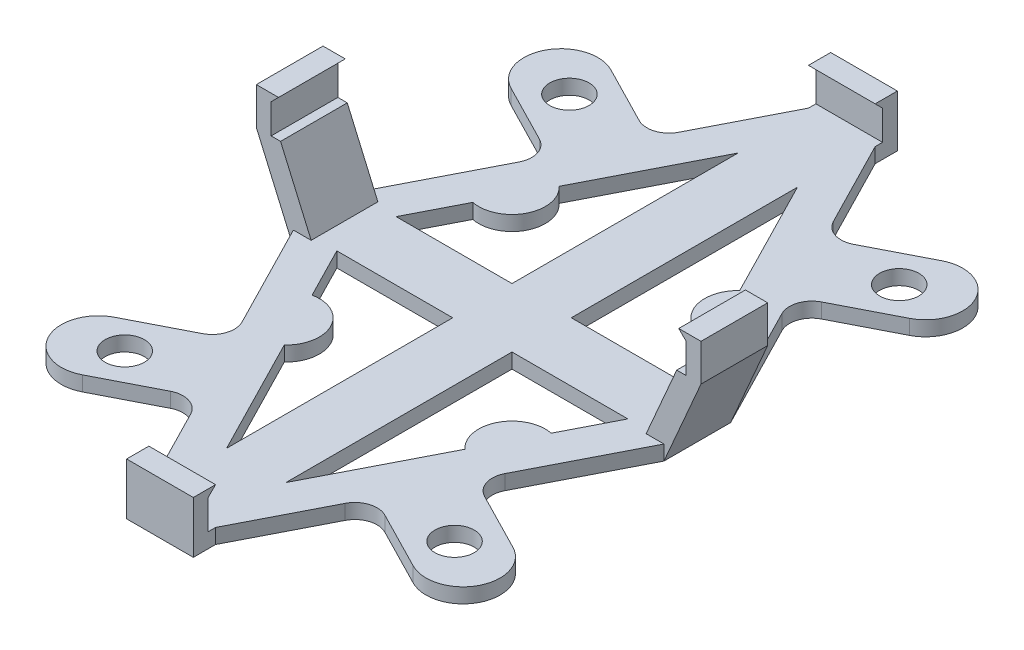
SolidWorks part; units mm, degrees
material "PLA"
ref_plane "Front Plane" through (0, 0, 0) normal (0, 0, 1) x (1, 0, 0)
ref_plane "Top Plane" through (0, 0, 0) normal (0, 1, 0) x (1, 0, 0)
ref_plane "Right Plane" through (0, 0, 0) normal (1, 0, 0) x (0, 0, -1)
sketch "Sketch1" plane through (0, 0, 0) normal (0, 1, 0) x (1, 0, 0)
  line L0 (-762.7074, 0) -> (37372.6612, 0) construction
  line L1 (0, -762.7074) -> (0, 37372.6612) construction
  line L2 (4.5, 47.5) -> (-4.5, 47.5)
  line L3 (-4.5, 47.5) -> (-4.5, 44.5)
  line L4 (-4.5, 44.5) -> (-10.429, 32.9312)
  line L6 (-25, 4.5) -> (-25, -4.5)
  line L7 (-4, 34.5129) -> (-12.1841, 18.544)
  line L8 (-19.6379, 4) -> (-4, 4)
  line L9 (-4, 4) -> (-4, 34.5129)
  line L10 (4, 4) -> (4, 34.5129)
  line L11 (19.6379, 4) -> (4, 4)
  line L12 (4, 34.5129) -> (12.1841, 18.544)
  line L13 (25, 4.5) -> (25, -4.5)
  line L15 (4.5, 44.5) -> (10.429, 32.9312)
  line L16 (4.5, 47.5) -> (4.5, 44.5)
  line L17 (4.5, -47.5) -> (4.5, -44.5)
  line L18 (4.5, -44.5) -> (10.429, -32.9312)
  line L20 (4, -34.5129) -> (12.1841, -18.544)
  line L21 (19.6379, -4) -> (4, -4)
  line L22 (4, -4) -> (4, -34.5129)
  line L23 (-4, -4) -> (-4, -34.5129)
  line L24 (-19.6379, -4) -> (-4, -4)
  line L25 (-4, -34.5129) -> (-12.1841, -18.544)
  line L27 (-4.5, -44.5) -> (-10.429, -32.9312)
  line L28 (-4.5, -47.5) -> (-4.5, -44.5)
  line L29 (4.5, -47.5) -> (-4.5, -47.5)
  line L30 (-14.4671, 31.6297) -> (-22.3279, 35.6583)
  line L31 (22.25, -30) -> (-22.25, -30) construction
  line L32 (22.25, -30) -> (22.25, 30) construction
  line L33 (22.25, 30) -> (-22.25, 30) construction
  line L34 (-22.25, -30) -> (-22.25, 30) construction
  line L35 (22.25, -30) -> (-22.25, 30) construction
  line L36 (22.25, 30) -> (-22.25, -30) construction
  line L37 (-22.3279, 35.6583) -> (-26.8888, 26.759) construction
  line L38 (-26.8888, 26.759) -> (-19.028, 22.7303)
  line L39 (-24.6083, 31.2086) -> (-22.25, 30) construction
  line L40 (-26.8888, -26.759) -> (-19.028, -22.7303)
  line L41 (-14.4671, -31.6297) -> (-22.3279, -35.6583)
  line L42 (14.4671, 31.6297) -> (22.3279, 35.6583)
  line L43 (26.8888, 26.759) -> (19.028, 22.7303)
  line L44 (14.4671, -31.6297) -> (22.3279, -35.6583)
  line L45 (26.8888, -26.759) -> (19.028, -22.7303)
  line L46 (11.9312, 30) -> (16.1479, 21.7724) construction
  line L47 (17.7265, 18.6923) -> (17.4906, 19.1525) construction
  line L48 (-11.9312, 30) -> (-16.1479, 21.7724) construction
  line L49 (-17.7265, 18.6923) -> (-17.4906, 19.1525) construction
  line L50 (-11.7973, 30.2614) -> (-11.9312, 30) construction
  line L51 (-16.1479, 21.7724) -> (-16.3582, 21.3621) construction
  line L52 (-11.9312, -30) -> (-16.1479, -21.7724) construction
  line L53 (-17.7265, -18.6923) -> (-17.4906, -19.1525) construction
  line L54 (-16.1479, -21.7724) -> (-16.3582, -21.3621) construction
  line L55 (-11.7973, -30.2614) -> (-11.9312, -30) construction
  line L56 (16.1479, 21.7724) -> (16.3582, 21.3621) construction
  line L57 (11.7973, 30.2614) -> (11.9312, 30) construction
  line L58 (11.9312, -30) -> (16.1479, -21.7724) construction
  line L59 (17.7265, -18.6923) -> (17.4906, -19.1525) construction
  line L60 (16.1479, -21.7724) -> (16.3582, -21.3621) construction
  line L61 (11.7973, -30.2614) -> (11.9312, -30) construction
  line L62 (16.1336, -10.8376) -> (19.6379, -4)
  line L63 (-15.25, 15.25) -> (15.25, 15.25) construction
  line L64 (-15.25, 15.25) -> (-15.25, -15.25) construction
  line L65 (-15.25, -15.25) -> (15.25, -15.25) construction
  line L66 (15.25, 15.25) -> (15.25, -10.75) construction
  line L67 (-15.25, 15.25) -> (14.3391, -14.3391) construction
  line L68 (-15.25, -15.25) -> (15.25, 15.25) construction
  line L69 (-13.8722, -15.25) -> (-14.3391, -14.3391) construction
  line L70 (-16.1336, -10.8376) -> (-19.6379, -4)
  line L71 (-16.1336, 10.8376) -> (-19.6379, 4)
  line L72 (16.1336, 10.8376) -> (19.6379, 4)
  line L73 (19.7264, -14.7899) -> (25, -4.5)
  line L74 (22.25, -9.8659) -> (19.7264, -14.7899) construction
  line L75 (17.4906, -19.1525) -> (22.25, -9.8659) construction
  line L76 (19.7264, 14.7899) -> (25, 4.5)
  line L77 (22.25, 9.8659) -> (19.7264, 14.7899) construction
  line L78 (17.4906, 19.1525) -> (22.25, 9.8659) construction
  line L79 (-19.7264, -14.7899) -> (-25, -4.5)
  line L80 (-22.25, -9.8659) -> (-19.7264, -14.7899) construction
  line L81 (-17.4906, -19.1525) -> (-17.7265, -18.6923) construction
  line L82 (-19.7264, 14.7899) -> (-25, 4.5)
  line L83 (-22.25, 9.8659) -> (-19.7264, 14.7899) construction
  line L84 (-17.4906, 19.1525) -> (-22.25, 9.8659) construction
  line L85 (-19.7264, -14.7899) -> (-22.25, -9.8659) construction
  line L86 (-17.7265, -18.6923) -> (-19.7264, -14.7899) construction
  line L87 (-17.7265, -18.6923) -> (-19.7264, -14.7899)
  line L88 (17.7265, -18.6923) -> (19.7264, -14.7899)
  line L89 (19.7264, 14.7899) -> (17.7265, 18.6923)
  line L90 (-19.7264, 14.7899) -> (-17.7265, 18.6923)
  circle A0 centre (-22.25, 30) radius 2.65
  arc A1 (-22.3279, 35.6583) -> (-26.8888, 26.759) centre (-24.6083, 31.2086) ccw
  circle A2 centre (-22.25, -30) radius 2.65
  arc A3 (-22.3279, -35.6583) -> (-26.8888, -26.759) centre (-24.6083, -31.2086) cw
  arc A4 (22.3279, 35.6583) -> (26.8888, 26.759) centre (24.6083, 31.2086) cw
  circle A5 centre (22.25, 30) radius 2.65
  circle A6 centre (22.25, -30) radius 2.65
  arc A7 (22.3279, -35.6583) -> (26.8888, -26.759) centre (24.6083, -31.2086) ccw
  arc A8 (14.4671, -31.6297) -> (10.429, -32.9312) centre (13.0988, -34.2995) ccw
  arc A9 (19.028, -22.7303) -> (17.7265, -18.6923) centre (20.3963, -20.0605) cw
  arc A10 (-10.429, -32.9312) -> (-14.4671, -31.6297) centre (-13.0988, -34.2995) ccw
  arc A11 (-17.7265, -18.6923) -> (-19.028, -22.7303) centre (-20.3963, -20.0605) cw
  arc A12 (-17.7265, 18.6923) -> (-19.028, 22.7303) centre (-20.3963, 20.0605) ccw
  arc A13 (-14.4671, 31.6297) -> (-10.429, 32.9312) centre (-13.0988, 34.2995) ccw
  arc A14 (14.4671, 31.6297) -> (10.429, 32.9312) centre (13.0988, 34.2995) cw
  arc A15 (19.028, 22.7303) -> (17.7265, 18.6923) centre (20.3963, 20.0605) ccw
  arc A16 (13.4822, -13.4822) -> (12.75, -15.25) centre (15.25, -15.25) ccw construction
  arc A17 (-12.75, -15.25) -> (-15.25, -12.75) centre (-15.25, -15.25) cw construction
  arc A18 (13.4822, 13.4822) -> (12.75, 15.25) centre (15.25, 15.25) cw construction
  arc A19 (-12.75, 15.25) -> (-15.25, 12.75) centre (-15.25, 15.25) ccw construction
  arc A20 (16.1336, -10.8376) -> (12.1841, -18.544) centre (15.25, -15.25) ccw
  circle A21 centre (15.25, -15.25) radius 4.5 construction
  arc A22 (-16.1336, -10.8376) -> (-12.1841, -18.544) centre (-15.25, -15.25) cw
  arc A23 (16.1336, 10.8376) -> (12.1841, 18.544) centre (15.25, 15.25) cw
  arc A24 (-16.1336, 10.8376) -> (-12.1841, 18.544) centre (-15.25, 15.25) ccw
  arc A25 (17.5478, -19.1191) -> (19.7264, -14.7899) centre (15.25, -15.25) ccw construction
  arc A26 (17.4906, 19.1525) -> (17.5478, 19.1191) centre (15.25, 15.25) cw construction
  arc A27 (-17.5478, 19.1191) -> (-19.7264, 14.7899) centre (-15.25, 15.25) ccw construction
  arc A28 (-17.4906, -19.1525) -> (-17.5478, -19.1191) centre (-15.25, -15.25) cw construction
  arc A29 (-17.5478, -19.1191) -> (-19.7264, -14.7899) centre (-15.25, -15.25) cw construction
  arc A30 (17.4906, -19.1525) -> (17.5478, -19.1191) centre (15.25, -15.25) ccw construction
  arc A31 (-13.4822, -13.4822) -> (-12.75, -15.25) centre (-15.25, -15.25) cw construction
  arc A32 (12.75, -15.25) -> (13.4822, -13.4822) centre (15.25, -15.25) ccw construction
  circle A33 centre (15.25, -15.25) radius 2.5 construction
  arc A34 (-15.25, -12.75) -> (-13.4822, -13.4822) centre (-15.25, -15.25) cw construction
  arc A35 (12.75, 15.25) -> (15.25, 12.75) centre (15.25, 15.25) cw construction
  arc A36 (17.5478, 19.1191) -> (19.7264, 14.7899) centre (15.25, 15.25) cw construction
  arc A37 (15.25, 12.75) -> (13.4822, 13.4822) centre (15.25, 15.25) cw construction
  arc A38 (-17.4906, 19.1525) -> (-17.5478, 19.1191) centre (-15.25, 15.25) ccw construction
  arc A39 (-13.4822, 13.4822) -> (-12.75, 15.25) centre (-15.25, 15.25) ccw construction
  arc A40 (-15.25, 12.75) -> (-13.4822, 13.4822) centre (-15.25, 15.25) ccw construction
  point P10 (0, 0)
  point P22 (0, 47.5)
  point P26 (25, 0)
  point P33 (-25, 0)
  point P36 (0, -47.5)
  point P37 (0, 0)
  point P132 (17.6408, -14.5191)
  dimension "D12" = 5.3
  dimension "D14" = 3
  dimension "D9" = 30.5
  dimension "D15" = 5
  dimension "D17" = 4.5
  dimension "D1" = 95
  dimension "D2" = 50
  dimension "D3" = 3
  dimension "D4" = 9
  dimension "D5" = 9
  dimension "D6" = 5
  dimension "D7" = 8
  dimension "D8" = 8
  dimension "D10" = 44.5
  dimension "D11" = 60
  dimension "D13" = 10
  dimension "D16" = 2
extrude "Boss-Extrude1" add sketch "Sketch1" along normal mid plane 2 contours A15 L43 A4 L42 A14 L15 L16 L2 L3 L4 A13 L30 A1 L38 A12 L49 L6 L53 A11 L40 A3 L41 A10 L27 L28 L29 L17 L18 A8 L44 A7 L45 A9 L59 L13 L47 A23 L72 L11 L10 L12 A22 L70 L24 L23 L25 A19
sketch "Sketch6" plane through (0, 0, 0) normal (1, 0, 0) x (0, 0, -1)
  line L0 (47.5, 1) -> (47.5, 6)
  line L1 (47.5, 6) -> (44.5, 6)
  line L2 (44.5, 6) -> (45.5, 5)
  line L3 (45.5, 5) -> (45.5, 1)
  line L4 (45.5, 1) -> (47.5, 1)
  line L6 (18.544, 1) -> (10.75, 1) construction
  line L7 (0, 9.075) -> (0, -9.075) construction
  line L8 (-45.5, 1) -> (-47.5, 1)
  line L9 (-45.5, 5) -> (-45.5, 1)
  line L10 (-44.5, 6) -> (-45.5, 5)
  line L11 (-47.5, 6) -> (-44.5, 6)
  line L12 (-47.5, 1) -> (-47.5, 6)
  line L14 (47.5, 1) -> (47.5, -1) construction
  dimension "D1" = 2
  dimension "D2" = 3
  dimension "D3" = 1
  dimension "D4" = 5
extrude "Boss-Extrude4" add sketch "Sketch6" along normal mid plane 9
sketch "Sketch4" plane through (0, 0, 0) normal (0, 0, 1) x (1, 0, 0)
  line L0 (30, 10.5) -> (30, 15.5)
  line L1 (30, 15.5) -> (27, 15.5)
  line L2 (27, 15.5) -> (28, 14.5)
  line L3 (28, 14.5) -> (28, 10.5)
  line L4 (28, 10.5) -> (30, 10.5) construction
  line L5 (28, 10.5) -> (26.7287, 10.5)
  line L6 (26.7287, 10.5) -> (22.5983, 1)
  line L7 (0, -9.075) -> (0, 9.075) construction
  line L8 (-28, 10.5) -> (-30, 10.5) construction
  line L9 (-28, 14.5) -> (-28, 10.5)
  line L10 (-27, 15.5) -> (-28, 14.5)
  line L11 (-30, 15.5) -> (-27, 15.5)
  line L12 (-30, 10.5) -> (-30, 15.5)
  line L14 (25, -1) -> (30, 10.5)
  line L16 (22.5983, 1) -> (25, 1)
  line L17 (25, 1) -> (25, -1)
  line L18 (25, 1) -> (25, -1) construction
  line L20 (-25, 1) -> (-25, -1)
  line L21 (-22.5983, 1) -> (-25, 1)
  line L22 (-25, -1) -> (-30, 10.5)
  line L23 (-26.7287, 10.5) -> (-22.5983, 1)
  line L24 (-28, 10.5) -> (-26.7287, 10.5)
  line L25 (16.1336, 1) -> (10.75, 1) construction
  dimension "D7" = 3
  dimension "D1" = 2
  dimension "D2" = 3
  dimension "D3" = 1
  dimension "D4" = 5
  dimension "D5" = 60
  dimension "D6" = 9.5
extrude "Boss-Extrude5" add sketch "Sketch4" along normal mid plane 9
sketch "Sketch7" plane through (0, 0, 0) normal (0, -1, 0) x (1, 0, 0)
  line L1 (-18.8, -31.75) -> (14.2, -31.75) construction
  line L2 (-18.8, -31.75) -> (-18.8, 16.25) construction
  line L3 (-18.8, 16.25) -> (14.2, 16.25) construction
  line L4 (14.2, -31.75) -> (14.2, 16.25) construction
  line L5 (-18.8, -31.75) -> (14.2, 16.25) construction
  line L6 (-18.8, 16.25) -> (14.2, -31.75) construction
  line L7 (-28, -35.25) -> (28, -35.25) construction
  line L8 (-28, -35.25) -> (-28, 35.25) construction
  line L9 (-28, 35.25) -> (28, 35.25) construction
  line L10 (28, -35.25) -> (28, 35.25) construction
  line L11 (-28, -35.25) -> (28, 35.25) construction
  line L12 (-28, 35.25) -> (28, -35.25) construction
  circle A0 centre (-18.8, 16.25) radius 1.5
  circle A1 centre (14.2, 16.25) radius 1.5
  circle A2 centre (14.2, -31.75) radius 1.5
  circle A3 centre (-18.8, -31.75) radius 1.5
  point P0 (-2.3, -7.75)
  point P11 (0, 0)
  dimension "D3" = 3
  dimension "D1" = 33
  dimension "D2" = 48
  dimension "D4" = 70.5
  dimension "D5" = 56
  dimension "D6" = 13.8
  dimension "D7" = 3.5
